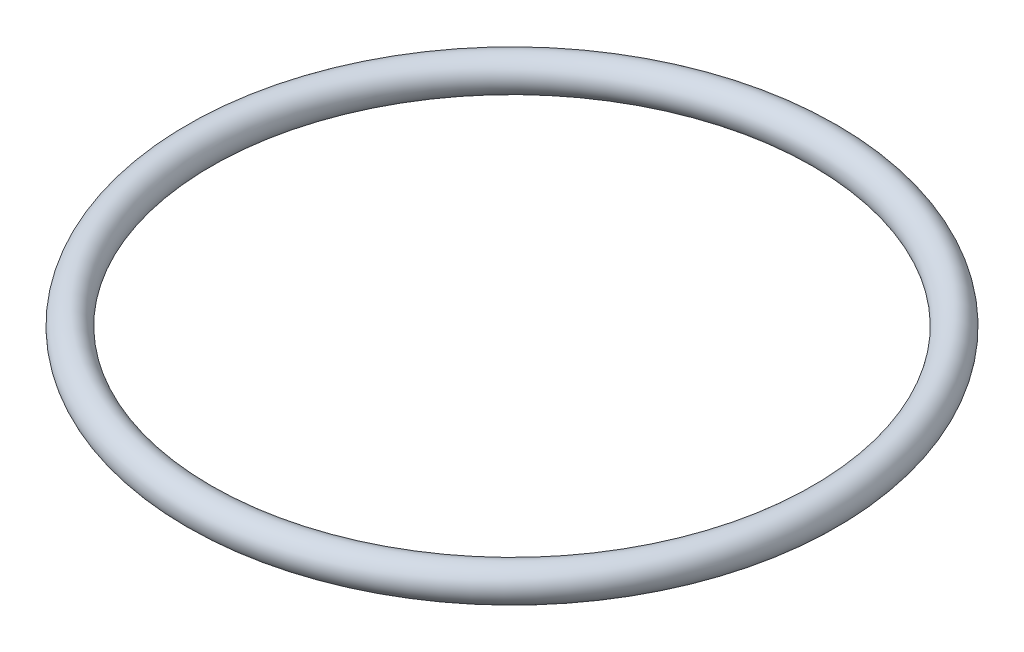
SolidWorks part; units mm, degrees
ref_plane "前视基准面" through (0, 0, 0) normal (0, 0, 1) x (1, 0, 0)
ref_plane "上视基准面" through (0, 0, 0) normal (0, 1, 0) x (1, 0, 0)
ref_plane "右视基准面" through (0, 0, 0) normal (1, 0, 0) x (0, 0, -1)
ref_axis "基准轴1" through (0, 11, 0) along (0, -1, 0)
sketch "草图1" plane through (0, 0, 0) normal (1, 0, 0) x (0, 0, -1)
  line L0 (11, 0) -> (-11, 0) construction
  circle A0 centre (-185, 0) radius 10
  point P2 (0, 0)
  dimension "D1" = 20
  dimension "D2" = 185
revolve "旋转1" add sketch "草图1" angle 360 about axis through (0, 11, 0) along (0, -1, 0)
